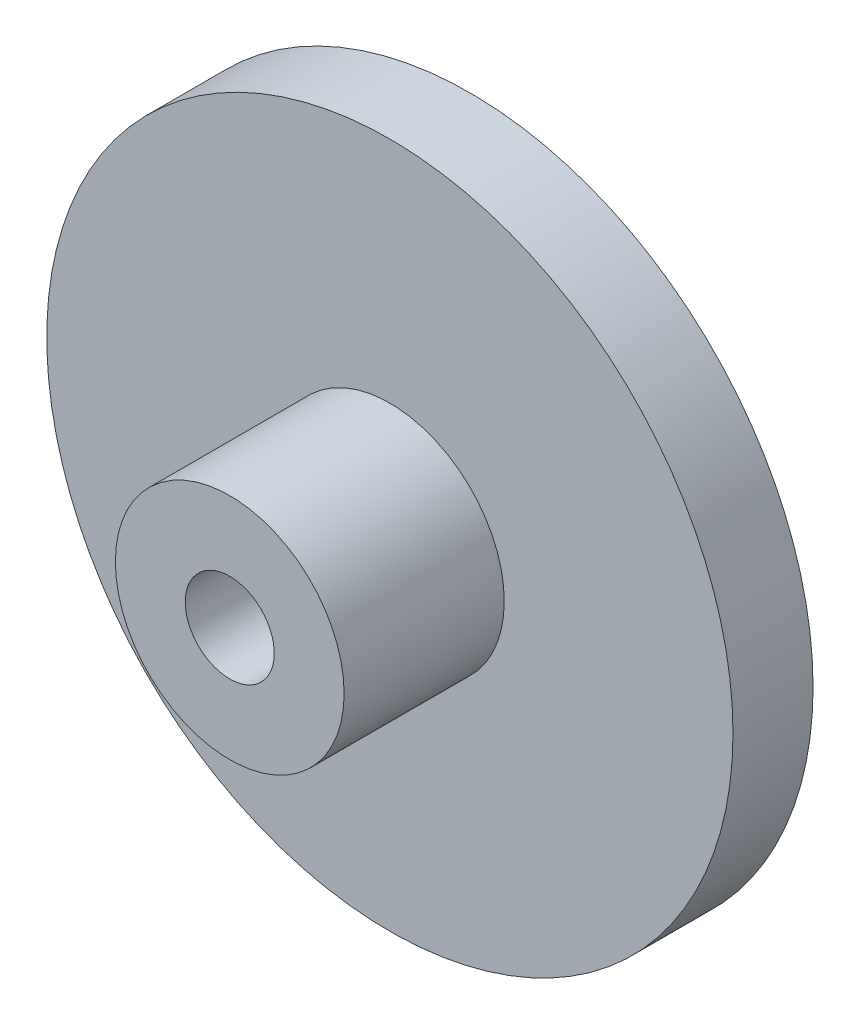
SolidWorks part; units mm, degrees
ref_plane "Alzado" through (0, 0, 0) normal (0, 0, 1) x (1, 0, 0)
ref_plane "Planta" through (0, 0, 0) normal (0, 1, 0) x (1, 0, 0)
ref_plane "Vista lateral" through (0, 0, 0) normal (1, 0, 0) x (0, 0, -1)
sketch "Croquis1" plane through (0, 0, 0) normal (0, 0, 1) x (1, 0, 0)
  circle A0 centre (0, 0) radius 15
  dimension "D1" = 30
extrude "Saliente-Extruir1" add sketch "Croquis1" along normal blind 3.5
sketch "Croquis2" plane through (0, 0, 3.5) normal (0, 0, 1) x (1, 0, 0)
  circle A0 centre (0, 0) radius 5
  dimension "D1" = 10
extrude "Saliente-Extruir2" add sketch "Croquis2" along normal blind 7
sketch "Croquis3" plane through (0, 0, 0) normal (0, 0, -1) x (-1, 0, 0)
  circle A0 centre (0, 0) radius 1.945
  dimension "D1" = 3.89
extrude "Cortar-Extruir1" cut sketch "Croquis3" against normal through all
